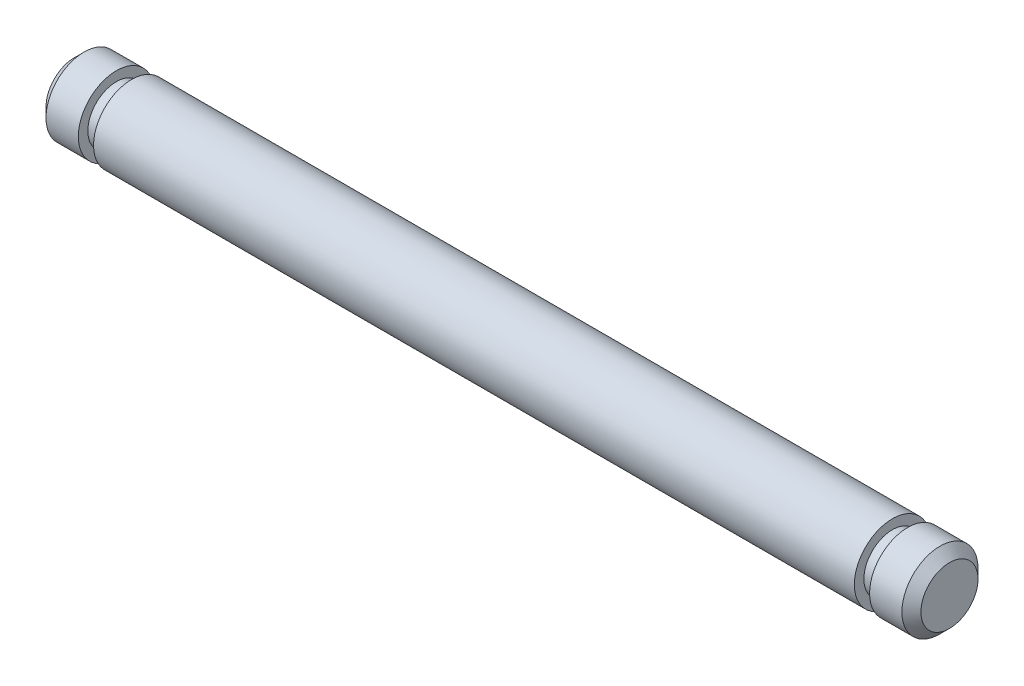
SolidWorks part; units mm, degrees
ref_plane "Front Plane" through (0, 0, 0) normal (0, 0, 1) x (1, 0, 0)
ref_plane "Top Plane" through (0, 0, 0) normal (0, 1, 0) x (1, 0, 0)
ref_plane "Right Plane" through (0, 0, 0) normal (1, 0, 0) x (0, 0, -1)
sketch "Sketch1" plane through (0, 0, 0) normal (1, 0, 0) x (0, 0, -1)
  circle A0 centre (0, 0) radius 2
  dimension "D1" = 4
extrude "Boss-Extrude1" add sketch "Sketch1" along normal mid plane 46
chamfer "Chamfer1" distance 0.5 angle 45 2 edges at (-23, 0, -2) (23, 0, -2)
sketch "Sketch2" plane through (-23, 0, 0) normal (-1, 0, 0) x (0, 0, 1)
  circle A0 centre (0, 0) radius 2 construction
  circle A1 centre (0, 0) radius 2
  circle A2 centre (0, 0) radius 1.5
  dimension "D1" = 3
extrude "Cut-Extrude1" cut sketch "Sketch2" along normal blind 0.8 from offset 3 offset against normal yes
mirror "Mirror2" about plane through (0, 0, 0) normal (1, 0, 0) of "Cut-Extrude1"
